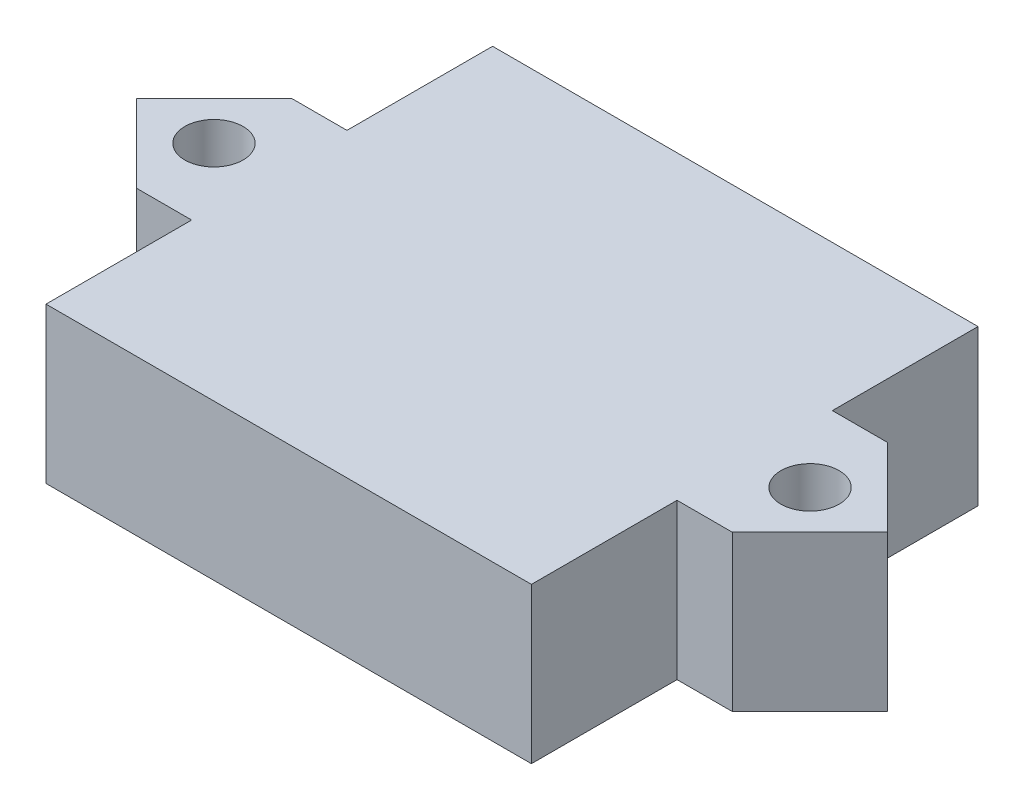
SolidWorks part; units mm, degrees
ref_plane "前视基准面" through (0, 0, 0) normal (0, 0, 1) x (1, 0, 0)
ref_plane "上视基准面" through (0, 0, 0) normal (0, 1, 0) x (1, 0, 0)
ref_plane "右视基准面" through (0, 0, 0) normal (1, 0, 0) x (0, 0, -1)
other "Configuration Table"
sketch "草图1" plane through (0, 0, 0) normal (0, 1, 0) x (1, 0, 0)
  line L0 (-19.35, 0) -> (-15.35, -4)
  line L1 (-15.35, -4) -> (-12.5, -4)
  line L2 (-12.5, -4) -> (-12.5, -12.5)
  line L3 (-12.5, -12.5) -> (12.5, -12.5)
  line L4 (12.5, -12.5) -> (12.5, -4)
  line L5 (12.5, -4) -> (15.35, -4)
  line L6 (15.35, -4) -> (19.35, 0)
  line L7 (19.35, 0) -> (15.35, 4)
  line L8 (15.35, 4) -> (12.5, 4)
  line L9 (12.5, 4) -> (12.5, 12.5)
  line L10 (12.5, 12.5) -> (-12.5, 12.5)
  line L11 (-12.5, 12.5) -> (-12.5, 4)
  line L12 (-12.5, 4) -> (-15.35, 4)
  line L13 (-15.35, 4) -> (-19.35, 0)
  circle A0 centre (-15.35, 0) radius 1.5
  circle A1 centre (15.35, 0) radius 1.5
extrude "外壳模块组合包络_厚度暂估8mm" add sketch "草图1" along normal blind 8
other "包络宽度25改23_非实测" face at (0, 4, -12.5) face at (0, 4, 12.5) parameters "D1"=1
